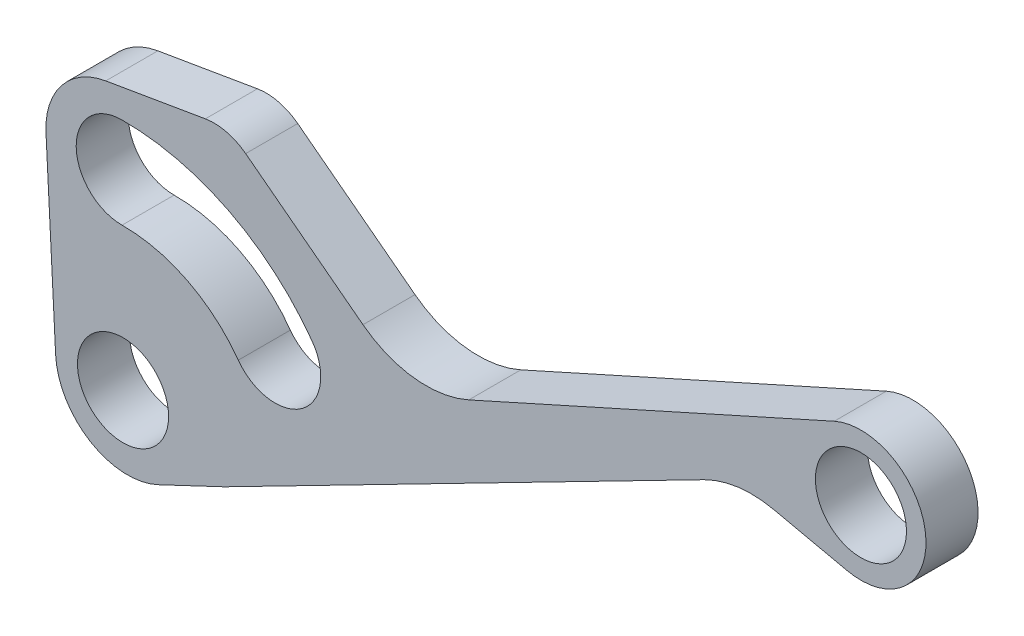
SolidWorks part; units mm, degrees
ref_plane "Front Plane" through (0, 0, 0) normal (0, 0, 1) x (1, 0, 0)
ref_plane "Top Plane" through (0, 0, 0) normal (0, 1, 0) x (1, 0, 0)
ref_plane "Right Plane" through (0, 0, 0) normal (1, 0, 0) x (0, 0, -1)
sketch "Sketch2" plane through (0, 0, 0) normal (0, 0, 1) x (1, 0, 0)
  line L0 (13.45, 15.25) -> (13.45, 6.55) construction
  line L1 (6.45, 15.25) -> (13.45, 15.25) construction
  line L2 (6.45, 15.25) -> (6.45, 6.4403) construction
  line L3 (6.45, -1.75) -> (13.45, -1.75) construction
  line L4 (13.45, 15.25) -> (13.45, -1.75) construction
  line L5 (13.45, 6.55) -> (23.95, 6.55) construction
  line L6 (-2.9597, 7.0942) -> (-2.5895, -0.1124)
  line L7 (1.3516, -2.4693) -> (3.8941, -1.2676)
  line L8 (23.95, 6.55) -> (28.35, 6.55) construction
  line L9 (28.35, 6.55) -> (28.35, 10.35) construction
  line L10 (27.811, 7.9088) -> (25.0059, 8.5282)
  line L11 (22.318, 8.1815) -> (3.8941, -1.2676)
  line L12 (13.2851, 6.3203) -> (27.3252, 12.6303)
  line L14 (9.2184, 6.7891) -> (4.7116, 10.229)
  line L15 (3.163, 10.6109) -> (-0.6627, 9.9607)
  line L16 (6.45, 2.6203) -> (6.45, -1.75) construction
  circle A0 centre (0, 0) radius 1.75
  arc A1 (-0.0621, 8.9725) -> (-0.0379, 5.4726) centre (-0.05, 7.2226) ccw
  circle A2 centre (23.95, 6.55) radius 1.875 construction
  arc A3 (4.4292, 3.2145) -> (7.2618, 5.2703) centre (5.8455, 4.2424) ccw
  arc A4 (4.4292, 3.2145) -> (-0.0379, 5.4726) centre (0, 0) ccw
  arc A5 (7.2618, 5.2703) -> (-0.0621, 8.9725) centre (0, 0) ccw
  arc A6 (4.7116, 10.229) -> (3.163, 10.6109) centre (3.4982, 8.6392) ccw
  circle A7 centre (28.35, 10.35) radius 1.75
  arc A8 (27.811, 7.9088) -> (27.3252, 12.6303) centre (28.35, 10.35) ccw
  arc A9 (9.2184, 6.7891) -> (13.2851, 6.3203) centre (11.6454, 9.9688) ccw
  arc A10 (25.0059, 8.5282) -> (22.318, 8.1815) centre (24.1434, 4.6223) ccw
  arc A14 (-2.5895, -0.1124) -> (1.3516, -2.4693) centre (0.1706, 0.0294) ccw
  arc A15 (-2.9597, 7.0942) -> (-0.6627, 9.9607) centre (-0.1996, 7.236) cw
  dimension "D1" = 3.5
  dimension "D2" = 3.5
  dimension "D4" = 6.5
  dimension "D5" = 7
  dimension "D6" = 17
  dimension "D7" = 6.45
  dimension "D8" = 1.75
  dimension "D11" = 3.75
  dimension "D12" = 3.5
  dimension "D9" = 8.7
  dimension "D13" = 2
  dimension "D17" = 3.5
  dimension "D18" = 5
  dimension "D19" = 4
  dimension "D3" = 7.2227
  dimension "D10" = 10.5
  dimension "D14" = 7.2227
  dimension "D15" = 4.4
  dimension "D16" = 3.8
extrude "Boss-Extrude1" add sketch "Sketch2" along normal blind 2
scale "Scale1" scale about centroid uniform scaling yes scale factor 2
